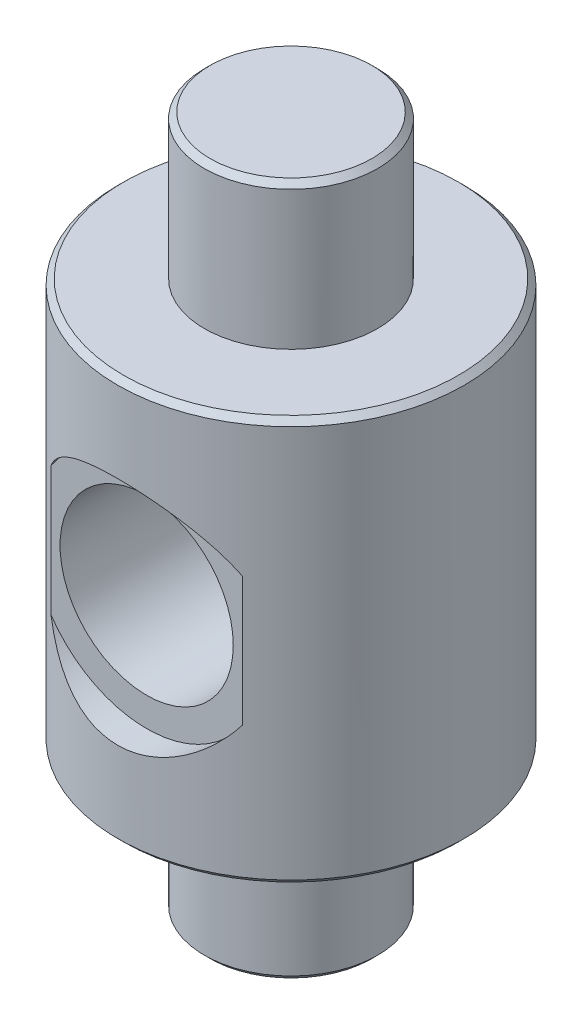
SolidWorks part; units mm, degrees
ref_plane "Front Plane" through (0, 0, 0) normal (0, 0, 1) x (1, 0, 0)
ref_plane "Top Plane" through (0, 0, 0) normal (0, 1, 0) x (1, 0, 0)
ref_plane "Right Plane" through (0, 0, 0) normal (1, 0, 0) x (0, 0, -1)
sketch "Sketch1" plane through (0, 0, 0) normal (0, 0, 1) x (1, 0, 0)
  line L0 (0, 0) -> (0, 12)
  line L1 (0, 12) -> (1.5, 12)
  line L2 (1.5, 12) -> (1.5, 9.5)
  line L3 (1.5, 9.5) -> (3, 9.5)
  line L4 (3, 9.5) -> (3, 2.5)
  line L5 (3, 2.5) -> (1.5, 2.5)
  line L6 (1.5, 2.5) -> (1.5, 0)
  line L7 (1.5, 0) -> (0, 0)
  point P3 (0, 0)
  point P10 (0, 0)
  dimension "D1" = 12
  dimension "D2" = 1.5
  dimension "D3" = 7
  dimension "D4" = 2.5
  dimension "D5" = 3
revolve "Revolve1" add sketch "Sketch1" angle 360 about L0
ref_plane "Plane1" through (0, 0, 3) normal (0, 0, 1) x (1, 0, 0)
sketch "Sketch2" plane through (0, 0, 3) normal (0, 0, 1) x (1, 0, 0)
  circle A0 centre (0, 6) radius 2
  point P2 (0, 0)
  dimension "D1" = 4
  dimension "D2" = 6
extrude "Cut-Extrude1" cut sketch "Sketch2" against normal blind 0.5
mirror "Mirror1" about plane through (0, 0, 0) normal (0, 0, 1) of "Cut-Extrude1"
sketch "Sketch3" plane through (0, 0, 2.5) normal (0, 0, 1) x (1, 0, 0)
  circle A0 centre (0, 6) radius 1.5
  arc A1 (1.6583, 7.118) -> (-1.6583, 7.118) centre (0, 6) ccw construction
  arc A2 (-1.6583, 4.882) -> (1.6583, 4.882) centre (0, 6) ccw construction
  point P5 (0, 8)
  point P6 (0, 4)
  point P7 (0, 0)
  dimension "D1" = 3
  dimension "D2" = 2
extrude "Cut-Extrude2" cut sketch "Sketch3" against normal through all
chamfer "Chamfer1" distance 0.1 angle 45 4 edges at (0, 0, -1.5) (0, 2.5, -3) (0, 9.5, -3) (0, 12, -1.5)
